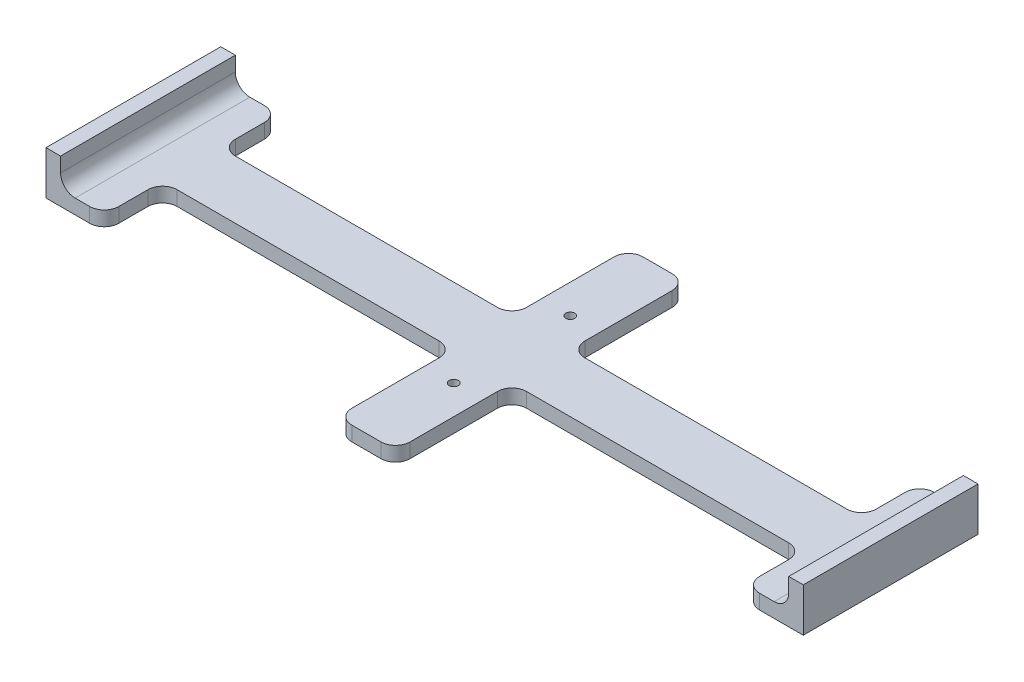
SolidWorks part; units mm, degrees
ref_plane "Front" through (0, 0, 0) normal (0, 0, 1) x (1, 0, 0)
ref_plane "Top" through (0, 0, 0) normal (0, 1, 0) x (1, 0, 0)
ref_plane "Right" through (0, 0, 0) normal (1, 0, 0) x (0, 0, -1)
sketch "Sketch1" plane through (0, 0, 0) normal (0, 1, 0) x (1, 0, 0)
  line L0 (-152.4, 0) -> (0, 0) construction
  line L1 (-12.7, 63.5) -> (12.7, 63.5)
  line L2 (-12.7, 63.5) -> (-12.7, -63.5)
  line L3 (-12.7, -63.5) -> (12.7, -63.5)
  line L4 (12.7, 63.5) -> (12.7, -63.5)
  line L5 (-12.7, 63.5) -> (12.7, -63.5) construction
  line L6 (-12.7, -63.5) -> (12.7, 63.5) construction
  line L7 (-139.7, 12.7) -> (139.7, 12.7)
  line L8 (-139.7, 12.7) -> (-139.7, -12.7)
  line L9 (-139.7, -12.7) -> (139.7, -12.7)
  line L10 (139.7, 12.7) -> (139.7, -12.7)
  line L11 (-139.7, 12.7) -> (139.7, -12.7) construction
  line L12 (-139.7, -12.7) -> (139.7, 12.7) construction
  line L13 (-165.1, 38.1) -> (-139.7, 38.1)
  line L14 (-165.1, 38.1) -> (-165.1, -38.1)
  line L15 (-165.1, -38.1) -> (-139.7, -38.1)
  line L16 (-139.7, 38.1) -> (-139.7, -38.1)
  line L17 (-165.1, 38.1) -> (-139.7, -38.1) construction
  line L18 (-165.1, -38.1) -> (-139.7, 38.1) construction
  line L19 (0, 63.5) -> (0, -63.5) construction
  line L20 (165.1, -38.1) -> (139.7, -38.1)
  line L21 (165.1, 38.1) -> (165.1, -38.1)
  line L22 (165.1, 38.1) -> (139.7, 38.1)
  line L23 (139.7, 38.1) -> (139.7, -38.1)
  point P0 (0, 0)
  point P6 (0, 0)
  point P11 (-152.4, 0)
  dimension "D1" = 127
  dimension "D2" = 25.4
  dimension "D3" = 25.4
  dimension "D4" = 25.4
  dimension "D5" = 76.2
  dimension "D6" = 330.2
extrude "Boss-Extrude1" add sketch "Sketch1" along normal mid plane 6.35 contours L16 L13 L14 L15 L8 | L8 L9 L2 L7 | L2 L7 L4 L1 | L10 L7 L4 L9 | L2 L9 L4 L7 | L9 L2 L3 L4 | L22 L23 L10 L20 L21
hole_wizard "5/32 (0.15625) Diameter Hole1" positions "Sketch2" profile "Sketch3" hole size "5/32" standard "ANSI Inch" end condition through all
sketch "Sketch2" plane through (0, 3.175, 0) normal (0, 1, 0) x (1, 0, 0)
  line L0 (0, 63.5) -> (0, 0) construction
  line L1 (-12.7, 63.5) -> (12.7, 63.5) construction
  line L3 (165.1, 0) -> (-165.1, 0) construction
  line L4 (165.1, 38.1) -> (165.1, -38.1) construction
  line L5 (-165.1, 38.1) -> (-165.1, -38.1) construction
  point P0 (0, 25.4)
  point P17 (0, -25.4)
  dimension "D1" = 50.8
sketch "Sketch3" plane through (0, 3.175, -25.4) normal (1, 0, 0) x (0, 0, 1)
  line L0 (0, 0) -> (0, 6.35)
  line L1 (0, 6.35) -> (1.9844, 6.35)
  line L2 (1.9844, 6.35) -> (1.9844, 0)
  line L5 (1.9844, 0) -> (0, 0)
  line L11 (0, -6.35) -> (0, 107.95) construction
  dimension "Thru Hole Dia." = 3.9688
  dimension "Thru Hole Depth" = 6.35
sketch "Sketch4" plane through (0, 3.175, 0) normal (0, 1, 0) x (1, 0, 0)
  line L1 (165.1, -38.1) -> (158.75, -38.1)
  line L2 (165.1, -38.1) -> (165.1, 38.1)
  line L3 (165.1, 38.1) -> (158.75, 38.1)
  line L4 (158.75, -38.1) -> (158.75, 38.1)
  line L5 (0, 63.5) -> (0, 0) construction
  line L6 (-12.7, 63.5) -> (12.7, 63.5) construction
  line L7 (-165.1, -38.1) -> (-158.75, -38.1)
  line L8 (-165.1, -38.1) -> (-165.1, 38.1)
  line L9 (-165.1, 38.1) -> (-158.75, 38.1)
  line L10 (-158.75, -38.1) -> (-158.75, 38.1)
  dimension "D1" = 6.35
extrude "Boss-Extrude2" add sketch "Sketch4" along normal blind 12.7
fillet "Fillet2" radius 6.35 18 edges at (-158.75, 3.175, 0) (158.75, 3.175, 0) (-139.7, 0, -38.1) (-139.7, 0, 38.1) (-139.7, 0, 12.7) (-12.7, 0, 12.7) (-12.7, 0, 63.5) (12.7, 0, 63.5) (12.7, 0, 12.7) (139.7, 0, 12.7) (139.7, 0, 38.1) (139.7, 0, -38.1) (139.7, 0, -12.7) (12.7, 0, -12.7) (12.7, 0, -63.5) (-12.7, 0, -63.5) (-139.7, 0, -12.7) (-12.7, 0, -12.7)
